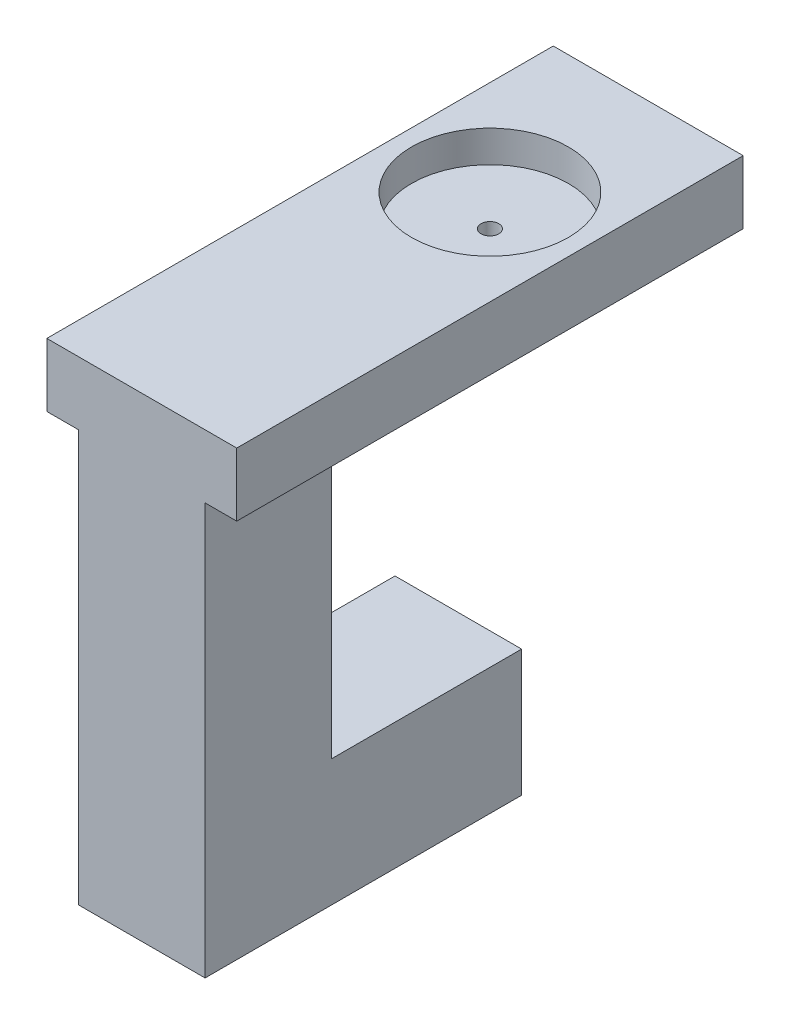
SolidWorks part; units mm, degrees
ref_plane "Alzado" through (0, 0, 0) normal (0, 0, 1) x (1, 0, 0)
ref_plane "Planta" through (0, 0, 0) normal (0, 1, 0) x (1, 0, 0)
ref_plane "Vista lateral" through (0, 0, 0) normal (1, 0, 0) x (0, 0, -1)
sketch "Croquis2" plane through (0, 0, 0) normal (0, 0, 1) x (1, 0, 0)
  line L1 (-10, 10) -> (10, 10)
  line L2 (-10, 10) -> (-10, -10)
  line L3 (-10, -10) -> (10, -10)
  line L4 (10, 10) -> (10, -10)
  line L5 (-10, 10) -> (10, -10) construction
  line L6 (-10, -10) -> (10, 10) construction
  point P0 (0, 0)
  dimension "D1" = 20
  dimension "D2" = 20
extrude "Saliente-Extruir1" add sketch "Croquis2" along normal blind 50
sketch "Croquis3" plane through (0, 10, 0) normal (0, 1, 0) x (1, 0, 0)
  line L0 (10, -50) -> (10, 0) construction
  line L1 (-10, -50) -> (10, -50)
  line L2 (-10, -50) -> (-10, -30)
  line L3 (-10, -30) -> (10, -30)
  line L4 (10, -50) -> (10, -30)
  dimension "D1" = 20
extrude "Saliente-Extruir2" add sketch "Croquis3" along normal blind 51
sketch "Croquis7" plane through (0, 0, 30) normal (0, 0, -1) x (-1, 0, 0)
  line L13 (-15, 65) -> (15, 65)
  line L14 (-15, 65) -> (-15, 55)
  line L15 (-15, 55) -> (15, 55)
  line L16 (15, 65) -> (15, 55)
  point P4 (0, 60)
  dimension "D2" = 30
extrude "Saliente-Extruir4" add sketch "Croquis7" along normal blind 60 and the other way blind 20
sketch "Croquis8" plane through (0, 65, 0) normal (0, 1, 0) x (1, 0, 0)
  circle A0 centre (0, 5) radius 1.4
  dimension "D2" = 2.8
extrude "Cortar-Extruir2" cut sketch "Croquis8" against normal blind 60
sketch "Croquis9" plane through (0, 65, 0) normal (0, 1, 0) x (1, 0, 0)
  circle A0 centre (0, 5) radius 12.395
  dimension "D1" = 24.79
extrude "Cortar-Extruir3" cut sketch "Croquis9" against normal blind 5
